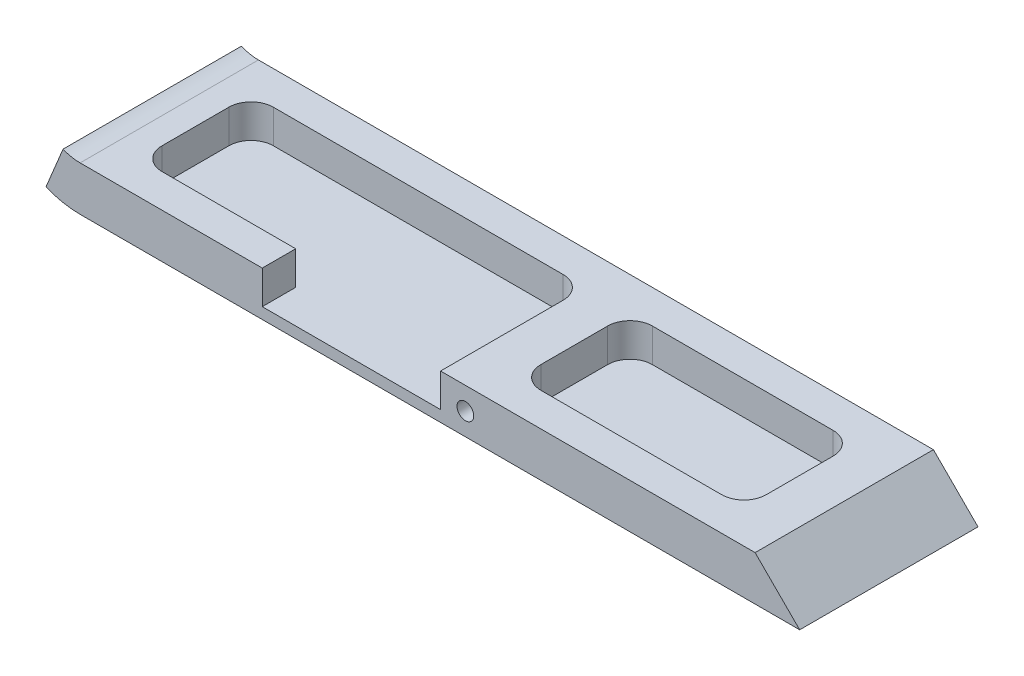
SolidWorks part; units mm, degrees
material "6061 Alloy"
ref_plane "Front Plane" through (0, 0, 0) normal (0, 0, 1) x (1, 0, 0)
ref_plane "Top Plane" through (0, 0, 0) normal (0, 1, 0) x (1, 0, 0)
ref_plane "Right Plane" through (0, 0, 0) normal (1, 0, 0) x (0, 0, -1)
sketch "Sketch1" plane through (0, 0, 0) normal (0, 0, 1) x (1, 0, 0)
  line L0 (0, 0) -> (215.5261, 0)
  line L1 (215.5261, 0) -> (202.8261, 12.7)
  line L2 (202.8261, 12.7) -> (5.2605, 12.7)
  line L3 (5.2605, 12.7) -> (0, 0)
  dimension "D1" = 215.5261
  dimension "D2" = 12.7
  dimension "D3" = 67.5
  dimension "D4" = 45
extrude "Extrude1" add sketch "Sketch1" along normal blind 50.8
sketch "Sketch2" plane through (0, 12.7, 0) normal (0, 1, 0) x (-1, 0, 0)
  line L0 (-202.8261, 50.8) -> (-5.2605, 50.8) construction
  line L1 (-113.2105, 50.8) -> (-62.4105, 50.8)
  line L2 (-113.2105, 50.8) -> (-113.2105, 15.875)
  line L3 (-106.8605, 9.525) -> (-24.3105, 9.525)
  line L4 (-62.4105, 50.8) -> (-62.4105, 41.275)
  line L5 (-5.2605, 50.8) -> (-5.2605, 0) construction
  line L6 (-62.4105, 41.275) -> (-24.3105, 41.275)
  line L7 (-17.9605, 34.925) -> (-17.9605, 15.875)
  line L8 (-202.8261, 50.8) -> (-202.8261, 0) construction
  line L9 (-132.2605, 9.525) -> (-183.7761, 9.525)
  line L10 (-125.9105, 15.875) -> (-125.9105, 34.925)
  line L11 (-132.2605, 41.275) -> (-183.7761, 41.275)
  line L12 (-190.1261, 15.875) -> (-190.1261, 34.925)
  arc A0 (-17.9605, 15.875) -> (-24.3105, 9.525) centre (-24.3105, 15.875) cw
  arc A1 (-24.3105, 41.275) -> (-17.9605, 34.925) centre (-24.3105, 34.925) cw
  arc A2 (-113.2105, 15.875) -> (-106.8605, 9.525) centre (-106.8605, 15.875) ccw
  arc A3 (-183.7761, 9.525) -> (-190.1261, 15.875) centre (-183.7761, 15.875) cw
  arc A4 (-132.2605, 9.525) -> (-125.9105, 15.875) centre (-132.2605, 15.875) ccw
  arc A5 (-125.9105, 34.925) -> (-132.2605, 41.275) centre (-132.2605, 34.925) ccw
  arc A6 (-183.7761, 41.275) -> (-190.1261, 34.925) centre (-183.7761, 34.925) ccw
  dimension "D6" = 6.35
  dimension "D9" = 6.35
  dimension "D1" = 9.525
  dimension "D2" = 41.275
  dimension "D3" = 107.95
  dimension "D4" = 50.8
  dimension "D5" = 12.7
  dimension "D7" = 12.7
  dimension "D8" = 12.7
extrude "Cut-Extrude1" cut sketch "Sketch2" against normal blind 9.525
sketch "Sketch3" plane through (0, 0, 0) normal (0, 0, -1) x (-1, 0, 0)
  line L0 (-202.8261, 12.7) -> (-5.2605, 12.7) construction
  circle A0 centre (-120.2761, 6.35) radius 2.3813
  dimension "D3" = 4.7625
  dimension "D1" = 95.25
  dimension "D2" = 6.35
extrude "Cut-Extrude2" cut sketch "Sketch3" against normal blind 15.875
sketch "Sketch4" plane through (0, 0, 50.8) normal (0, 0, 1) x (1, 0, 0)
  circle A0 centre (120.2761, 6.35) radius 2.3813
  circle A1 centre (120.2761, 6.35) radius 2.3813 construction
  dimension "D1" = 4.7625
extrude "Cut-Extrude3" cut sketch "Sketch4" against normal blind 15.875
sketch "Sketch5" plane through (0, 0, 50.8) normal (0, 0, 1) x (1, 0, 0)
  line L0 (0, 0) -> (215.5261, 0) construction
  line L1 (5.2605, 12.7) -> (0, 0) construction
  line L2 (0.8009, 1.9335) -> (0, 0)
  line L3 (0, 0) -> (10.521, 0)
  arc A0 (10.521, 0) -> (0.8009, 1.9335) centre (10.521, 25.4) cw
  dimension "D1" = 25.4
extrude "Cut-Extrude4" cut sketch "Sketch5" against normal through all
sketch "Sketch6" plane through (0, 0, 50.8) normal (0, 0, 1) x (1, 0, 0)
  line L0 (62.4105, 12.7) -> (5.2605, 12.7) construction
  line L1 (5.6609, 13.6667) -> (5.2605, 12.7)
  line L2 (5.2605, 12.7) -> (10.521, 12.7)
  line L3 (5.2605, 12.7) -> (0.8009, 1.9335) construction
  arc A0 (10.521, 12.7) -> (5.6609, 13.6667) centre (10.521, 25.4) cw
  arc A1 (0.8009, 1.9335) -> (10.521, 0) centre (10.521, 25.4) ccw construction
extrude "Extrude2" add sketch "Sketch6" against normal up to surface (50.8 mm away) up to face at (117.8949, 6.35, 0)
